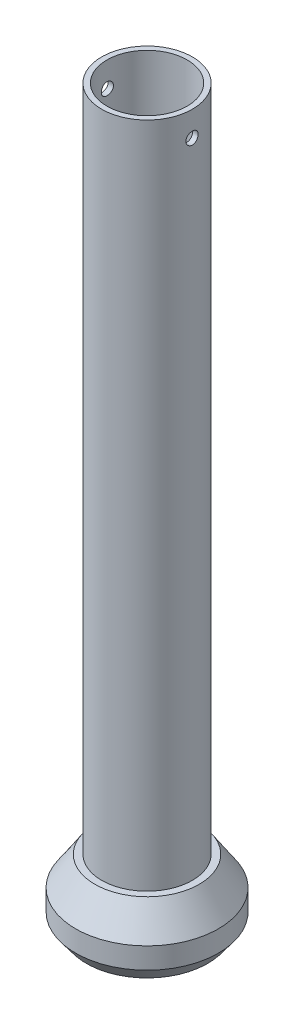
SolidWorks part; units mm, degrees
ref_plane "Front Plane" through (0, 0, 0) normal (0, 0, 1) x (1, 0, 0)
ref_plane "Top Plane" through (0, 0, 0) normal (0, 1, 0) x (1, 0, 0)
ref_plane "Right Plane" through (0, 0, 0) normal (1, 0, 0) x (0, 0, -1)
sketch "Sketch1" plane through (0, 0, 0) normal (0, 1, 0) x (1, 0, 0)
  circle A0 centre (0, 0) radius 12.7
  circle A1 centre (0, 0) radius 11.227
extrude "Boss-Extrude1" add sketch "Sketch1" along normal blind 205
sketch "Sketch2" plane through (0, 0, 0) normal (0, 0, 1) x (1, 0, 0)
  line L0 (0, 0) -> (17, 0)
  line L1 (17, 0) -> (20, 4)
  line L2 (20, 4) -> (20, 9.9)
  line L3 (20, 9.9) -> (14.605, 18)
  line L4 (14.605, 18) -> (0, 18)
  line L5 (0, 18) -> (0, 0)
  line L6 (0, -10) -> (0, 50) construction
revolve "Revolve1" add sketch "Sketch2" angle 360 about L6
sketch "Sketch3" plane through (0, 0, 0) normal (1, 0, 0) x (0, 0, -1)
  circle A0 centre (0, 198) radius 1.7
extrude "Cut-Extrude1" cut sketch "Sketch3" against normal through all and the other way through all
